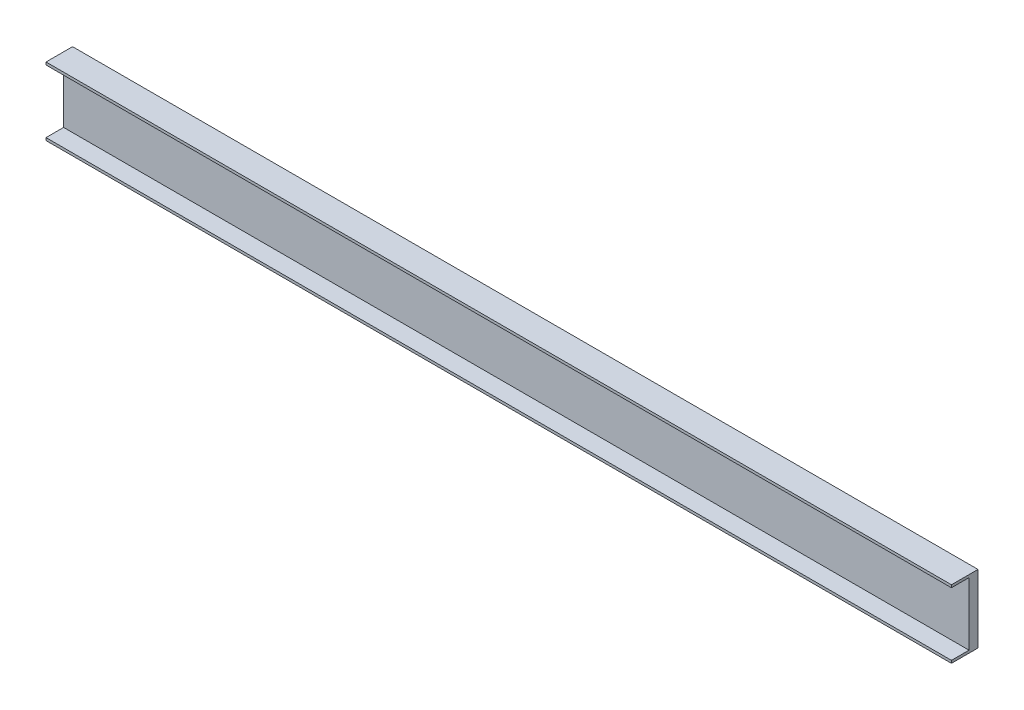
SolidWorks part; units mm, degrees
ref_plane "前视" through (0, 0, 0) normal (0, 0, 1) x (1, 0, 0)
ref_plane "上视" through (0, 0, 0) normal (0, 1, 0) x (1, 0, 0)
ref_plane "右视" through (0, 0, 0) normal (1, 0, 0) x (0, 0, -1)
sketch "草图1" plane through (0, 0, 0) normal (0, 0, 1) x (1, 0, 0)
  line L0 (0, 280.187) -> (0, -298.191) construction
  line L1 (-2057.2074, 0) -> (2116.7847, 0) construction
  line L2 (2116.7847, 80) -> (-2430.1435, 80) construction
  line L3 (-1995, 150) -> (1995, 150)
  line L5 (-1995, -150) -> (1995, -150)
  line L6 (1995, 150) -> (1995, -150)
  line L7 (-2430.1435, -80) -> (2116.7847, -80) construction
  line L8 (1940, 266.4652) -> (1940, -249.2739) construction
  line L9 (1860, -249.2739) -> (1860, 266.4652) construction
  line L10 (1060, 266.4652) -> (1060, -361.7988) construction
  line L11 (1780, 266.4652) -> (1780, -249.2739) construction
  line L12 (1780, -249.2739) -> (1700, -249.2739) construction
  line L13 (1700, -249.2739) -> (1700, 266.4652) construction
  line L14 (1540, 266.4652) -> (1540, -361.7988) construction
  line L15 (1380, 266.4652) -> (1380, -361.7988) construction
  line L16 (1220, -361.7988) -> (1220, 266.4652) construction
  line L17 (980, -361.7988) -> (980, 266.4652) construction
  line L18 (740, -361.7988) -> (740, 464.33) construction
  line L19 (820, 266.4652) -> (820, -361.7988) construction
  line L20 (580, -361.7988) -> (580, 266.4652) construction
  line L21 (420, -361.7988) -> (420, 266.4652) construction
  line L22 (300, -298.191) -> (300, 266.4652) construction
  line L23 (60, 280.187) -> (60, -298.191) construction
  line L24 (140, 280.187) -> (140, -298.191) construction
  line L25 (220, -298.191) -> (220, 280.187) construction
  line L26 (-1995, 150) -> (-1995, -150)
  dimension "D1" = 3990
  dimension "D2" = 300
  dimension "D3" = 70
  dimension "D4" = 80
  dimension "D5" = 55
  dimension "D6" = 80
  dimension "D7" = 80
  dimension "D8" = 80
  dimension "D9" = 455
  dimension "D10" = 160
  dimension "D11" = 160
  dimension "D12" = 160
  dimension "D13" = 80
  dimension "D14" = 160
  dimension "D15" = 80
  dimension "D16" = 160
  dimension "D17" = 160
  dimension "D18" = 120
  dimension "D19" = 60
  dimension "D20" = 80
  dimension "D21" = 80
extrude "基体-拉伸" add sketch "草图1" along normal blind 39.5
sketch "草图2" plane through (0, 0, 39.5) normal (0, 0, 1) x (1, 0, 0)
  line L0 (1995, -150) -> (1995, 150) construction
  line L1 (-1995, 150) -> (1995, 150)
  line L2 (-1995, 150) -> (-1995, 138.5)
  line L3 (-1995, 138.5) -> (1995, 138.5)
  line L4 (1995, 150) -> (1995, 138.5)
  line L5 (0, 0) -> (2507.3409, 0) construction
  line L6 (1995, -150) -> (1995, -138.5)
  line L7 (-1995, -138.5) -> (1995, -138.5)
  line L8 (-1995, -150) -> (-1995, -138.5)
  line L9 (-1995, -150) -> (1995, -150)
  dimension "D1" = 11.5
extrude "凸台-拉伸1" add sketch "草图2" along normal blind 77.5
sketch "草图3" plane through (0, 0, 0) normal (0, 0, -1) x (-1, 0, 0)
  line L0 (0, 0) -> (2381.8358, 0) construction
  line L1 (0, 348.8193) -> (0, -302.4645) construction
  line L2 (1300, 348.8193) -> (1300, -385.903) construction
  line L3 (1995, 150) -> (1995, -150) construction
  line L4 (900, 237.7997) -> (900, -385.903) construction
  line L5 (1265, 115) -> (1335, 115)
  line L6 (1265, 115) -> (1265, -115)
  line L7 (1265, -115) -> (1335, -115)
  line L8 (1335, 115) -> (1335, -115)
  line L9 (865, 115) -> (935, 115)
  line L10 (865, 115) -> (865, -115)
  line L11 (865, -115) -> (935, -115)
  line L12 (935, 115) -> (935, -115)
  line L13 (500, -385.903) -> (500, 237.7997) construction
  line L14 (-1265, 115) -> (-1335, 115)
  line L15 (535, -115) -> (465, -115)
  line L16 (535, -115) -> (535, 115)
  line L17 (535, 115) -> (465, 115)
  line L18 (465, -115) -> (465, 115)
  line L19 (-1335, 115) -> (-1335, -115)
  line L20 (-1265, 115) -> (-1265, -115)
  line L21 (-1265, -115) -> (-1335, -115)
  line L22 (-865, -115) -> (-935, -115)
  line L23 (-935, 115) -> (-935, -115)
  line L24 (-865, 115) -> (-935, 115)
  line L25 (-865, 115) -> (-865, -115)
  line L26 (-535, -115) -> (-535, 115)
  line L27 (-535, -115) -> (-465, -115)
  line L28 (-465, -115) -> (-465, 115)
  line L29 (-535, 115) -> (-465, 115)
  dimension "D1" = 695
  dimension "D2" = 70
  dimension "D3" = 230
  dimension "D4" = 400
  dimension "D5" = 70
  dimension "D6" = 230
  dimension "D7" = 400
  dimension "D8" = 70
  dimension "D9" = 230
extrude "凸台-拉伸2" add sketch "草图3" along normal blind 16
